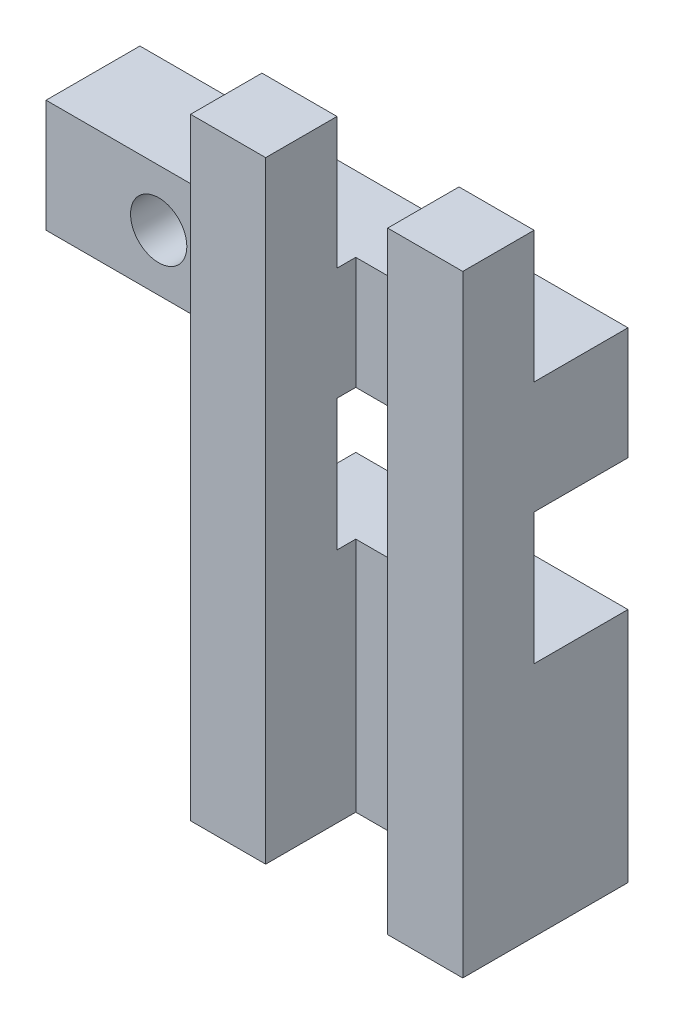
SolidWorks part; units mm, degrees
ref_plane "前视基准面" through (0, 0, 0) normal (0, 0, 1) x (1, 0, 0)
ref_plane "上视基准面" through (0, 0, 0) normal (0, 1, 0) x (1, 0, 0)
ref_plane "右视基准面" through (0, 0, 0) normal (1, 0, 0) x (0, 0, -1)
other "Configuration Table"
sketch "草图1" plane through (0, 0, 0) normal (0, 0, 1) x (1, 0, 0)
  line L1 (0, 0) -> (26, 0)
  line L2 (0, 0) -> (0, -6)
  line L3 (0, -6) -> (26, -6)
  line L4 (26, 0) -> (26, -6)
  circle A0 centre (6, -3) radius 1.5
  dimension "D4" = 3
  dimension "D1" = 26
  dimension "D2" = 6
  dimension "D3" = 6
  dimension "D5" = 3
extrude "凸台-拉伸1" add sketch "草图1" along normal blind 5
sketch "草图2" plane through (0, 0, 5) normal (0, 0, 1) x (1, 0, 0)
  line L0 (-2.6727, 7) -> (49997.3273, 7) construction
  line L1 (6, -3) -> (50006, -3) construction
  line L2 (26, -6) -> (26, 0) construction
  line L3 (26, 7) -> (22, 7)
  line L4 (26, 7) -> (26, -25.6)
  line L5 (26, -25.6) -> (22, -25.6)
  line L6 (22, 7) -> (22, -25.6)
  line L7 (15.5, 7) -> (11.5, 7)
  line L8 (15.5, 7) -> (15.5, -25.6)
  line L9 (15.5, -25.6) -> (11.5, -25.6)
  line L10 (11.5, 7) -> (11.5, -25.6)
  dimension "D1" = 4
  dimension "D2" = 6.5
  dimension "D3" = 4
  dimension "D4" = 32.6
  dimension "D5" = 10
extrude "凸台-拉伸2" add sketch "草图2" along normal blind 3.8
sketch "草图3" plane through (0, 0, 5) normal (0, 0, 1) x (1, 0, 0)
  line L0 (15.5, -25.6) -> (15.5, 7) construction
  line L1 (15.5, 0.5) -> (22, 0.5)
  line L2 (15.5, 0.5) -> (15.5, -6)
  line L3 (15.5, -6) -> (22, -6)
  line L4 (22, 0.5) -> (22, -6)
extrude "切除-拉伸1" cut sketch "草图3" against normal blind 1
sketch "草图4" plane through (0, 0, 5) normal (0, 0, -1) x (-1, 0, 0)
  line L0 (-6, -3) -> (49994, -3) construction
  line L1 (-34.6246, -13) -> (49965.3754, -13) construction
  line L2 (-11.5, -6) -> (-11.5, -25.6) construction
  line L3 (-26, -25.6) -> (-11.5, -25.6)
  line L4 (-26, -25.6) -> (-26, -13)
  line L5 (-26, -13) -> (-11.5, -13)
  line L6 (-11.5, -25.6) -> (-11.5, -13)
  dimension "D1" = 10
extrude "凸台-拉伸3" add sketch "草图4" along normal blind 5
sketch "草图5" plane through (0, 0, 5) normal (0, 0, 1) x (1, 0, 0)
  line L0 (15.5, -25.6) -> (15.5, 7) construction
  line L1 (15.5, -13) -> (22, -13)
  line L2 (15.5, -13) -> (15.5, -25.6)
  line L3 (15.5, -25.6) -> (22, -25.6)
  line L4 (22, -13) -> (22, -25.6)
  line L5 (15.5, -13) -> (22, -13) construction
extrude "切除-拉伸2" cut sketch "草图5" against normal blind 1
